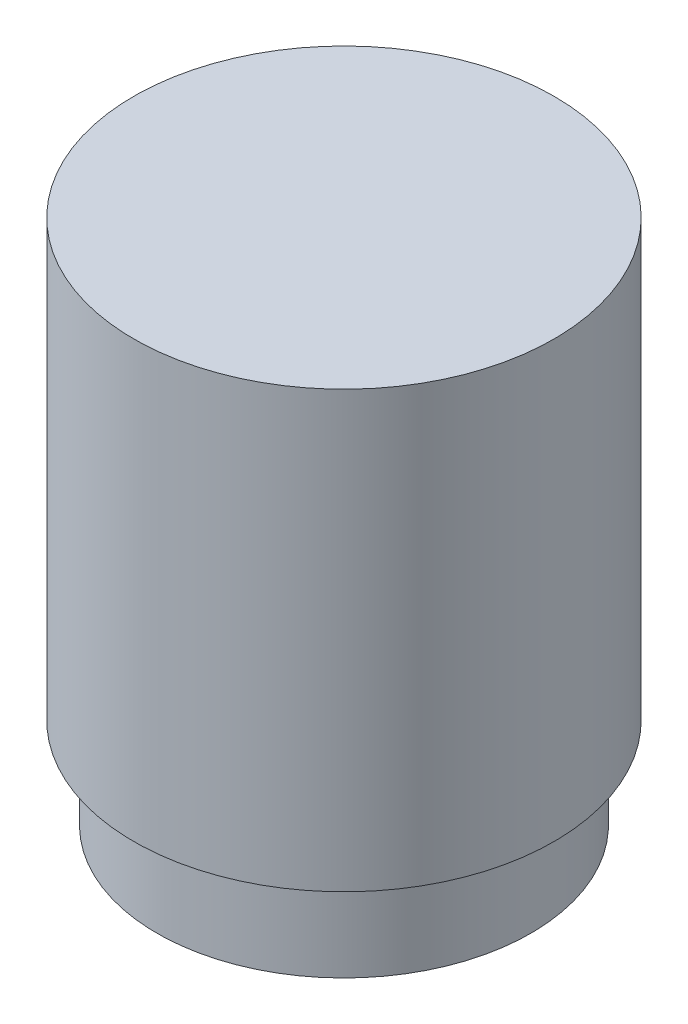
SolidWorks part; units mm, degrees
ref_plane "Front Plane" through (0, 0, 0) normal (0, 0, 1) x (1, 0, 0)
ref_plane "Top Plane" through (0, 0, 0) normal (0, 1, 0) x (1, 0, 0)
ref_plane "Right Plane" through (0, 0, 0) normal (1, 0, 0) x (0, 0, -1)
sketch "Sketch1" plane through (0, 0, 0) normal (1, 0, 0) x (0, 0, -1)
  line L0 (-3, 4) -> (-4.75, 4)
  line L1 (-4.75, 4) -> (-4.75, 0)
  line L2 (-4.75, 0) -> (-5.65, 0)
  line L3 (-5.65, 0) -> (-5.65, 2.75)
  line L4 (-5.65, 2.75) -> (-6.35, 2.75)
  line L5 (-6.35, 2.75) -> (-6.35, 15.9)
  line L6 (-6.35, 15.9) -> (0, 15.9)
  line L7 (0, 15.9) -> (0, 13.46)
  line L8 (0, 13.46) -> (-3, 13.46)
  line L9 (-3, 13.46) -> (-3, 4)
  line L10 (0, 0) -> (0, 13.5415) construction
  dimension "D1" = 12.7
  dimension "D2" = 11.3
  dimension "D3" = 9.5
  dimension "D4" = 6
  dimension "D5" = 13.46
  dimension "D6" = 15.9
  dimension "D7" = 4
  dimension "D8" = 2.75
revolve "Revolve1" add sketch "Sketch1" angle 360 about L10
